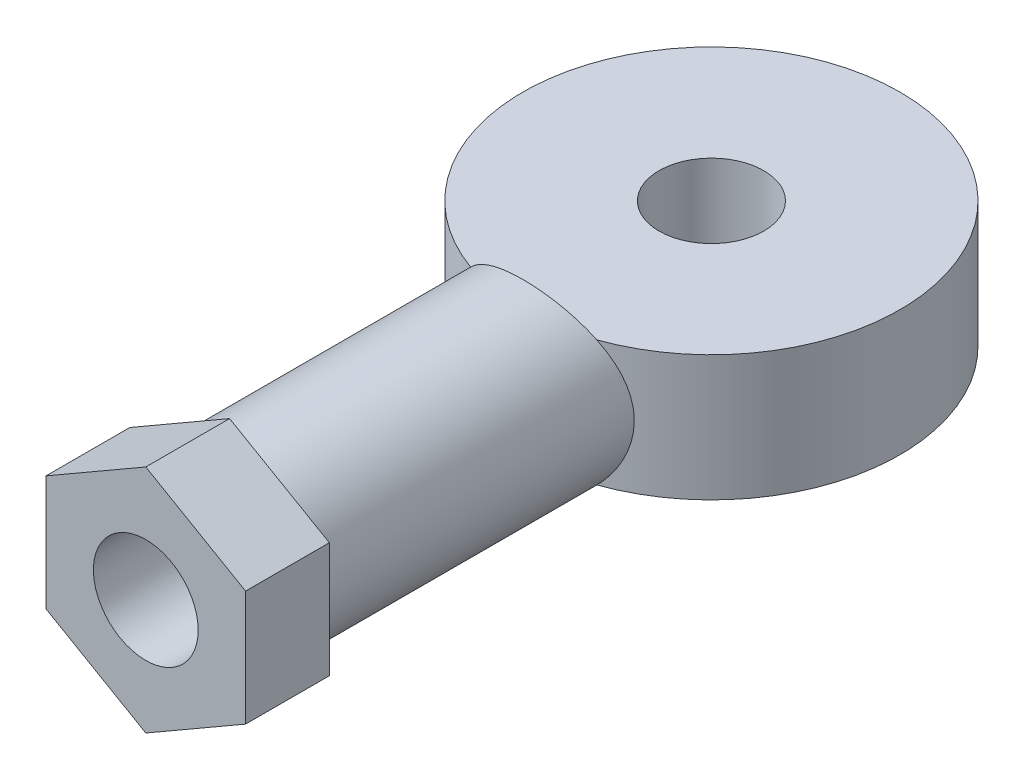
SolidWorks part; units mm, degrees
ref_plane "前视基准面" through (0, 0, 0) normal (0, 0, 1) x (1, 0, 0)
ref_plane "上视基准面" through (0, 0, 0) normal (0, 1, 0) x (1, 0, 0)
ref_plane "右视基准面" through (0, 0, 0) normal (1, 0, 0) x (0, 0, -1)
sketch "草图1" plane through (0, 0, 0) normal (0, 1, 0) x (1, 0, 0)
  circle A0 centre (0, 0) radius 9
  circle A1 centre (0, 0) radius 2.5
  dimension "D1" = 18
  dimension "D2" = 5
extrude "凸台-拉伸1" add sketch "草图1" along normal blind 6
ref_plane "基准面1" through (0, 0, 23) normal (0, 0, 1) x (1, 0, 0)
sketch "草图2" plane through (0, 0, 23) normal (0, 0, 1) x (1, 0, 0)
  line L0 (-9, 0) -> (9, 0) construction
  circle A0 centre (0, 3) radius 4.25
  dimension "D1" = 8.5
  dimension "D2" = 3
extrude "凸台-拉伸2" add sketch "草图2" against normal blind 18
sketch "草图3" plane through (0, 6, 0) normal (0, 1, 0) x (1, 0, 0)
  circle A0 centre (0, 0) radius 9
extrude "切除-拉伸1" cut sketch "草图3" along normal through all
sketch "草图4" plane through (0, 0, 0) normal (0, -1, 0) x (1, 0, 0)
  circle A0 centre (0, 0) radius 9
extrude "切除-拉伸2" cut sketch "草图4" along normal through all
sketch "草图5" plane through (0, 0, 23) normal (0, 0, 1) x (1, 0, 0)
  line L1 (0, 8.5) -> (-4.7631, 5.75)
  line L2 (-4.7631, 5.75) -> (-4.7631, 0.25)
  line L3 (-4.7631, 0.25) -> (0, -2.5)
  line L4 (0, -2.5) -> (4.7631, 0.25)
  line L5 (4.7631, 0.25) -> (4.7631, 5.75)
  line L6 (4.7631, 5.75) -> (0, 8.5)
extrude "凸台-拉伸3" add sketch "草图5" along normal blind 4
sketch "草图6" plane through (0, 0, 27) normal (0, 0, 1) x (1, 0, 0)
  circle A0 centre (0, 3) radius 2.5
  dimension "D1" = 5
extrude "切除-拉伸3" cut sketch "草图6" against normal blind 15
cosmetic thread "装饰螺纹线1" parameters "D1"=12, "D2"=6
